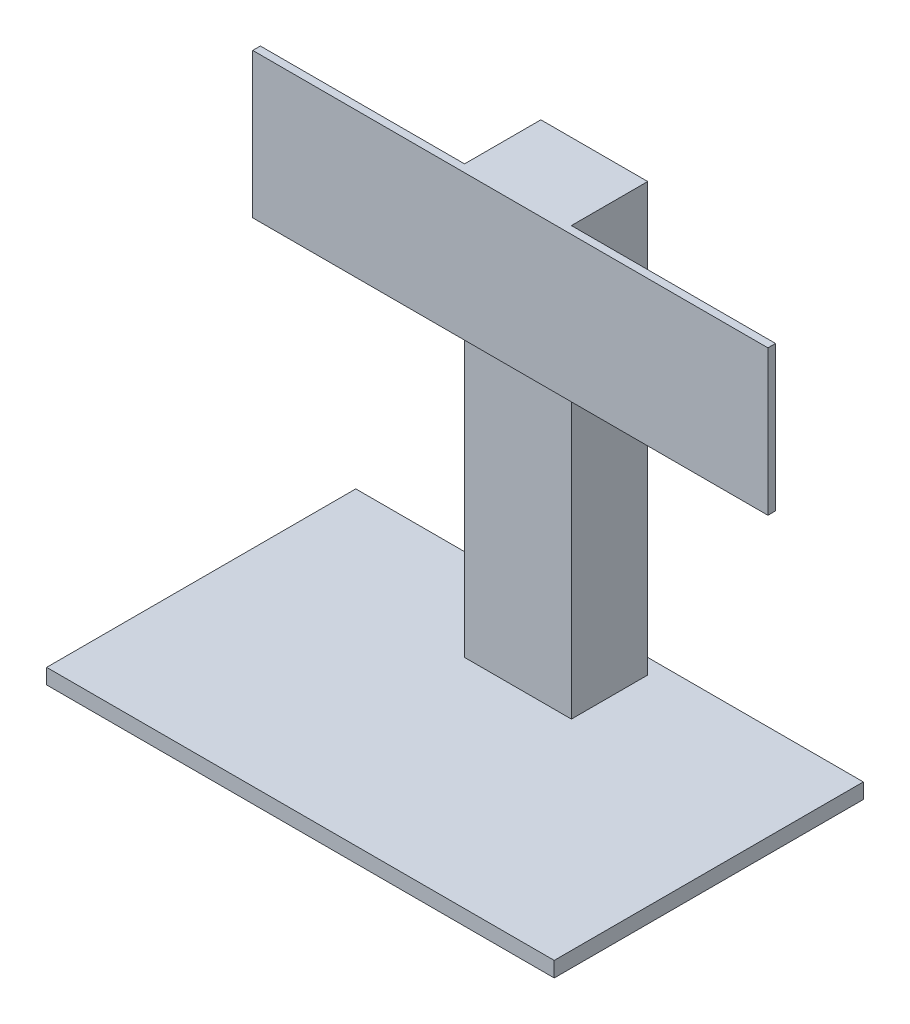
SolidWorks part; units mm, degrees
ref_plane "Front" through (0, 0, 0) normal (0, 0, 1) x (1, 0, 0)
ref_plane "Top" through (0, 0, 0) normal (0, 1, 0) x (1, 0, 0)
ref_plane "Right" through (0, 0, 0) normal (1, 0, 0) x (0, 0, -1)
sketch "Sketch2" plane through (0, 0, 0) normal (0, 1, 0) x (1, 0, 0)
  line L1 (211.1375, -128.5875) -> (-211.1375, -128.5875)
  line L2 (211.1375, -128.5875) -> (211.1375, 128.5875)
  line L3 (211.1375, 128.5875) -> (-211.1375, 128.5875)
  line L4 (-211.1375, -128.5875) -> (-211.1375, 128.5875)
  line L5 (0, 128.5875) -> (0, -128.5875) construction
  line L6 (211.1375, 0) -> (-211.1375, 0) construction
  point P0 (0, 0)
  dimension "D1" = 422.275
  dimension "D2" = 257.175
extrude "Boss-Extrude1" add sketch "Sketch2" along normal blind 12.7
sketch "Sketch3" plane through (0, 12.7, 0) normal (0, 1, 0) x (1, 0, 0)
  line L0 (0, 52.3875) -> (0, 0) construction
  line L1 (-44.45, 52.3875) -> (44.45, 52.3875)
  line L2 (-44.45, 52.3875) -> (-44.45, 115.8875)
  line L3 (-44.45, 115.8875) -> (44.45, 115.8875)
  line L4 (44.45, 52.3875) -> (44.45, 115.8875)
  line L5 (0, 115.8875) -> (0, 52.3875) construction
  line L6 (-44.45, 84.1375) -> (44.45, 84.1375) construction
  line L7 (211.1375, 128.5875) -> (-211.1375, 128.5875) construction
  point P0 (0, 84.1375)
  point P4 (0, 118.4928)
  dimension "D1" = 88.9
  dimension "D2" = 63.5
  dimension "D3" = 12.7
extrude "Boss-Extrude2" add sketch "Sketch3" along normal blind 355.6
sketch "Sketch4" plane through (0, 0, -52.3875) normal (0, 0, 1) x (1, 0, 0)
  line L0 (-44.45, 368.3) -> (44.45, 368.3) construction
  line L1 (-214.3125, 247.65) -> (214.3125, 247.65)
  line L2 (-214.3125, 247.65) -> (-214.3125, 368.3)
  line L3 (-214.3125, 368.3) -> (214.3125, 368.3)
  line L4 (214.3125, 247.65) -> (214.3125, 368.3)
  line L5 (0, 368.3) -> (0, 247.65) construction
  line L6 (-214.3125, 307.975) -> (214.3125, 307.975) construction
  point P0 (0, 307.975)
  point P4 (0, 469.9)
  dimension "D1" = 428.625
  dimension "D2" = 120.65
extrude "Boss-Extrude3" add sketch "Sketch4" along normal blind 6.35
